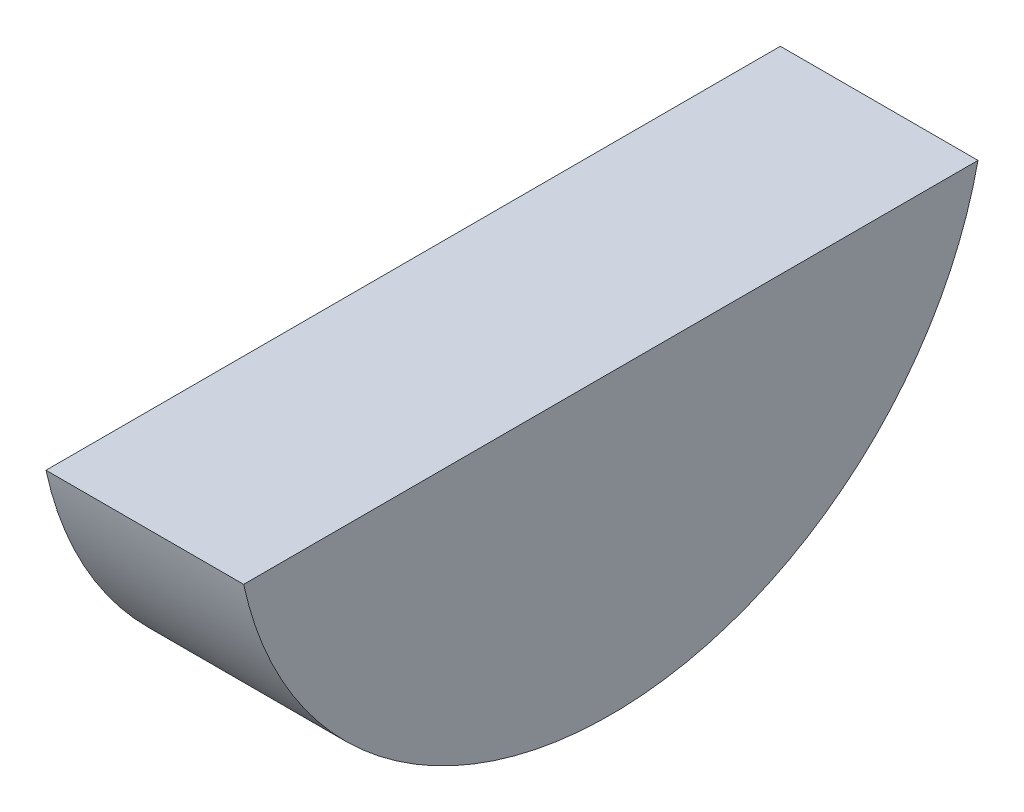
SolidWorks part; units mm, degrees
ref_plane "Спереди" through (0, 0, 0) normal (0, 0, 1) x (1, 0, 0)
ref_plane "Сверху" through (0, 0, 0) normal (0, 1, 0) x (1, 0, 0)
ref_plane "Справа" through (0, 0, 0) normal (1, 0, 0) x (0, 0, -1)
other "Configuration Table"
sketch "Эскиз1" plane through (0, 0, 0) normal (1, 0, 0) x (0, 0, -1)
  line L0 (0, 0) -> (0, 7.5) construction
  line L2 (-9.2871, 7.5) -> (9.2871, 7.5)
  arc A1 (-9.2871, 7.5) -> (9.2871, 7.5) centre (0, 9.5) ccw
  dimension "D1" = 9.5
  dimension "D2" = 9.2871
extrude "Бобышка-Вытянуть1" add sketch "Эскиз1" along normal blind 5
